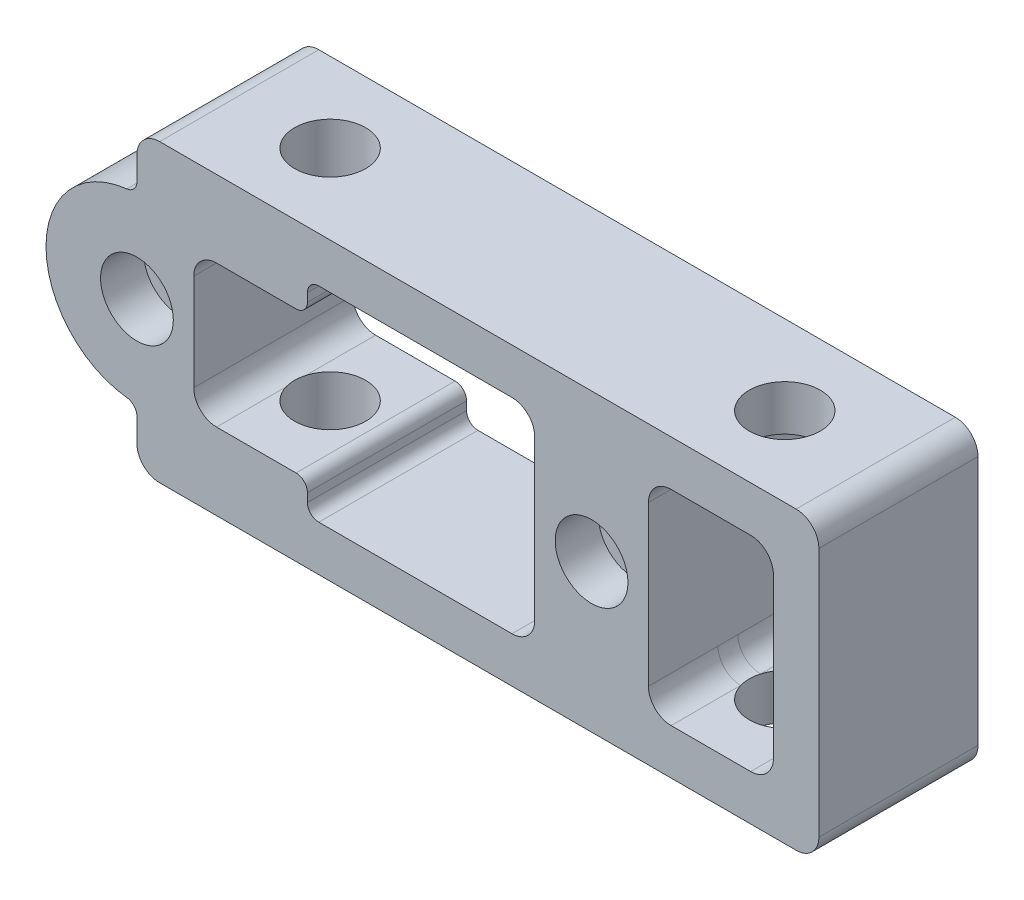
SolidWorks part; units mm, degrees
material "6061-T6 (SS)"
ref_plane "X-Y Datum" through (0, 0, 0) normal (0, 0, 1) x (1, 0, 0)
ref_plane "X-Z Datum" through (0, 0, 0) normal (0, 1, 0) x (1, 0, 0)
ref_plane "Y-Z Datum" through (0, 0, 0) normal (1, 0, 0) x (0, 0, -1)
other "Center of Mass"
other "Graphic1"
other "Graphic (Closed) -1"
other "Graphic2"
other "Graphic (Closed) -2"
other "Graphic3"
other "Graphic (Closed) -3"
sketch "Sketch1" plane through (0, 0, 0) normal (0, 1, 0) x (1, 0, 0)
  line L0 (101.6, 8.89) -> (76.2, 8.89) construction
  line L1 (101.6, 17.78) -> (0, 17.78)
  line L2 (101.6, 17.78) -> (101.6, 0)
  line L3 (101.6, 0) -> (0, 0)
  line L5 (0, 31.6293) -> (0, -17.6841) construction
  line L6 (0, 17.78) -> (0, 0)
  line L7 (76.2, 8.89) -> (25.4, 8.89) construction
  line L8 (25.4, 8.89) -> (0, 8.89) construction
  circle A0 centre (76.2, 8.89) radius 3.9688
  circle A1 centre (25.4, 8.89) radius 3.9687
  point P12 (50.8, 8.89)
  point P13 (50.8, 17.78)
  dimension "D3" = 7.9375
  dimension "D1" = 101.6
  dimension "D2" = 17.78
  dimension "D4" = 50.8
extrude "Boss-Extrude1" add sketch "Sketch1" against normal blind 33.02
sketch "Sketch2" plane through (0, 0, 0) normal (0, 0, 1) x (1, 0, 0)
  line L4 (0, -33.02) -> (0, 0) construction
  line L5 (0, -33.02) -> (101.6, -33.02) construction
  line L8 (101.6, -33.02) -> (101.6, 0) construction
  circle A0 centre (63.5, -16.51) radius 2.4892
  circle A1 centre (12.7, -16.51) radius 2.4892
  dimension "D3" = 4.9784
  dimension "D1" = 12.7
  dimension "D5" = 16.51
  dimension "D6" = 38.1
  dimension "D2" = 16.51
extrude "Cut-Extrude1" cut sketch "Sketch2" against normal up to surface (17.78 mm away) up to face at (50.8, -16.51, -17.78)
sketch "Sketch3" plane through (0, 0, 0) normal (0, 0, 1) x (1, 0, 0)
  circle A0 centre (63.5, -16.51) radius 4.064
  circle A3 centre (12.7, -16.51) radius 4.064
  circle A4 centre (12.7, -16.51) radius 2.4892 construction
  point P5 (0, 0)
  dimension "D1" = 8.128
extrude "Cut-Extrude2" cut sketch "Sketch3" against normal blind 4.826
ref_plane "Plane1" through (0, -16.51, 0) normal (0, 1, 0) x (1, 0, 0)
ref_plane "Plane2" through (0, -16.51, 0) normal (0, 1, 0) x (1, 0, 0)
sketch "Sketch5" plane through (0, 0, 0) normal (0, 0, 1) x (1, 0, 0)
  line L8 (0, -33.02) -> (101.6, -33.02) construction
  line L18 (0, -33.02) -> (0, 0) construction
  line L19 (50.8, 0) -> (50.8, -33.02) construction
  line L20 (0, 0) -> (101.6, 0) construction
  line B0 (12.7, -5.1508) -> (12.7, 0)
  line B1 (0, 0) -> (12.7, 0)
  line B2 (0, -33.02) -> (0, 0)
  line B3 (12.7, -33.02) -> (0, -33.02)
  line B4 (12.7, -27.8692) -> (12.7, -33.02)
  arc B5 (12.7, -5.1508) -> (11.5711, -6.4129) centre (11.43, -5.1508) cw
  arc B6 (12.7, -27.8692) -> (11.5711, -26.6071) centre (11.43, -27.8692) ccw
  arc B7 (11.5711, -26.6071) -> (11.5711, -6.4129) centre (12.7, -16.51) cw
  line B8 (88.9, -5.1508) -> (88.9, 0)
  line B9 (101.6, 0) -> (88.9, 0)
  line B10 (101.6, -33.02) -> (101.6, 0)
  line B11 (88.9, -33.02) -> (101.6, -33.02)
  line B12 (88.9, -27.8692) -> (88.9, -33.02)
  arc B13 (88.9, -5.1508) -> (90.0289, -6.4129) centre (90.17, -5.1508) ccw
  arc B14 (88.9, -27.8692) -> (90.0289, -26.6071) centre (90.17, -27.8692) cw
  arc B15 (90.0289, -26.6071) -> (90.0289, -6.4129) centre (88.9, -16.51) ccw
sketch_block_instance "Block2-1"
sketch_block "Block2"
sketch_block_instance "Block2-2"
extrude "Cut-Extrude3" cut sketch "Sketch5" against normal through all
fillet "Fillet1" radius 2.54 4 edges at (12.7, 0, -8.89) (88.9, 0, -8.89) (88.9, -33.02, -8.89) (12.7, -33.02, -8.89)
ref_point "Point1"
ref_point "Point2"
sketch "Sketch6" plane through (0, 0, 0) normal (0, 0, 1) x (1, 0, 0)
  line L0 (50.8, 0) -> (50.8, -33.02) construction
  line L1 (15.24, 0) -> (86.36, 0) construction
  line L2 (15.24, -33.02) -> (86.36, -33.02) construction
  line L3 (12.7, -30.48) -> (12.7, -27.8692) construction
  line L5 (19.05, -21.9075) -> (19.05, -11.1125)
  line L7 (57.15, -25.4) -> (57.15, -7.62)
  line L8 (69.85, -5.08) -> (69.85, -27.94)
  line L9 (69.85, -27.94) -> (83.82, -27.94)
  line L10 (83.82, -27.94) -> (83.82, -5.08)
  line L11 (83.82, -5.08) -> (69.85, -5.08)
  line L12 (88.9, -5.1508) -> (88.9, -27.8692)
  line L13 (88.9, -27.8692) -> (99.8485, -27.8692)
  line L14 (99.8485, -27.8692) -> (99.8485, -5.1508)
  line L15 (99.8485, -5.1508) -> (88.9, -5.1508)
  line L16 (21.59, -24.4475) -> (31.75, -24.4475)
  line L17 (31.75, -24.4475) -> (31.75, -27.94)
  line L18 (31.75, -27.94) -> (54.61, -27.94)
  line L19 (21.59, -8.5725) -> (31.75, -8.5725)
  line L20 (31.75, -8.5725) -> (31.75, -5.08)
  line L21 (31.75, -5.08) -> (54.61, -5.08)
  arc A0 (21.59, -24.4475) -> (19.05, -21.9075) centre (21.59, -21.9075) cw
  arc A1 (54.61, -27.94) -> (57.15, -25.4) centre (54.61, -25.4) ccw
  arc A2 (54.61, -5.08) -> (57.15, -7.62) centre (54.61, -7.62) cw
  arc A3 (19.05, -11.1125) -> (21.59, -8.5725) centre (21.59, -11.1125) cw
  point P6 (50.8, -16.51)
  point P23 (19.05, -16.51)
  point P30 (69.85, -16.51)
  point P33 (57.15, -16.51)
  point P34 (0, 0)
  point P37 (0, 0)
  dimension "D3" = 2.54
  dimension "D1" = 38.1
  dimension "D2" = 3.4925
  dimension "D4" = 6.35
  dimension "D5" = 12.7
  dimension "D6" = 22.86
  dimension "D7" = 13.97
  dimension "D8" = 16.51
  dimension "D9" = 3.4925
  dimension "D10" = 10.16
  dimension "D11" = 10.16
extrude "Cut-Extrude4" cut sketch "Sketch6" against normal through all
fillet "Fillet2" radius 2.54 4 edges at (69.85, -27.94, -8.89) (83.82, -27.94, -8.89) (83.82, -5.08, -8.89) (69.85, -5.08, -8.89)
fillet "Fillet3" radius 1.27 4 edges at (31.75, -27.94, -8.89) (31.75, -24.4475, -8.89) (31.75, -5.08, -8.89) (31.75, -8.5725, -8.89)
